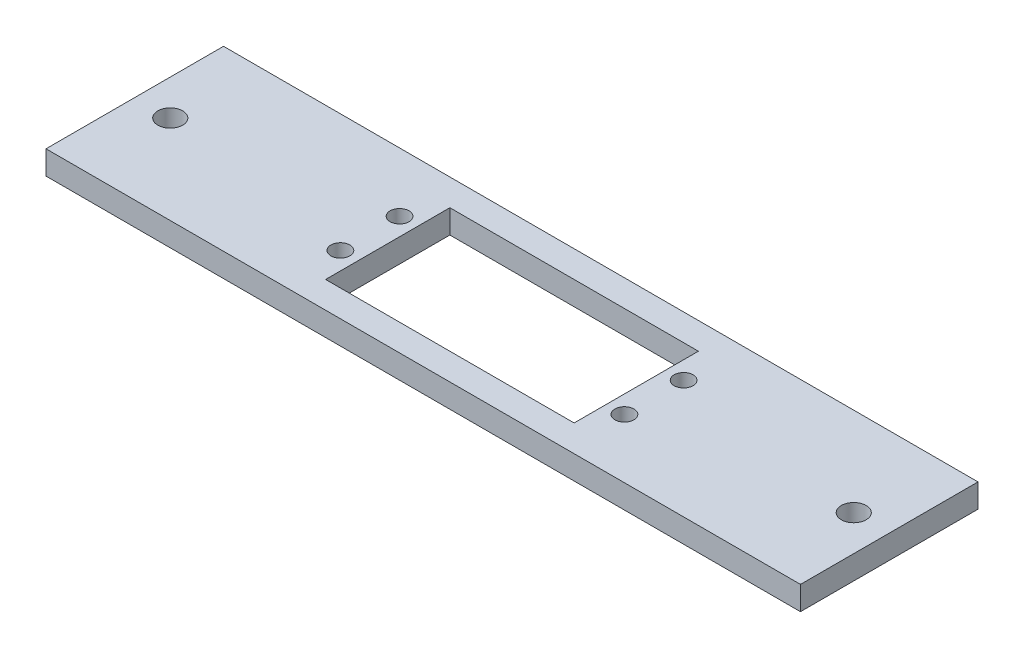
SolidWorks part; units mm, degrees
material "Balsa"
ref_plane "Front Plane" through (0, 0, 0) normal (0, 0, 1) x (1, 0, 0)
ref_plane "Top Plane" through (0, 0, 0) normal (0, 1, 0) x (1, 0, 0)
ref_plane "Right Plane" through (0, 0, 0) normal (1, 0, 0) x (0, 0, -1)
sketch "Sketch1" plane through (0, 0, 0) normal (0, 1, 0) x (1, 0, 0)
  line L0 (-21, 10.5) -> (-27.75, 10.5) construction
  line L1 (-21, -10.5) -> (21, -10.5)
  line L2 (-21, -10.5) -> (-21, 10.5)
  line L3 (-21, 10.5) -> (21, 10.5)
  line L4 (21, -10.5) -> (21, 10.5)
  line L5 (-21, -10.5) -> (21, 10.5) construction
  line L6 (-21, 10.5) -> (21, -10.5) construction
  line L7 (-27.75, 10.5) -> (-27.75, -10.5) construction
  line L8 (-27.75, -10.5) -> (-21, -10.5) construction
  line L9 (0, 10.5) -> (0, -10.5) construction
  line L10 (27.75, -10.5) -> (21, -10.5) construction
  line L11 (27.75, 10.5) -> (27.75, -10.5) construction
  line L12 (21, 10.5) -> (27.75, 10.5) construction
  line L13 (-53.9162, 0) -> (53.9162, 0) construction
  line L14 (0, 15) -> (0, -15) construction
  line L15 (-63.75, 15) -> (63.75, 15)
  line L16 (-63.75, 15) -> (-63.75, -15)
  line L17 (-63.75, -15) -> (63.75, -15)
  line L18 (63.75, 15) -> (63.75, -15)
  line L19 (-63.75, 0) -> (63.75, 0) construction
  circle A0 centre (-57.75, 0) radius 2.1
  circle A1 centre (57.75, 0) radius 2.1
  point P0 (0, 0)
  point P14 (0, 0)
  point P27 (0, 0)
  dimension "D4" = 4.2
  dimension "D1" = 21
  dimension "D2" = 42
  dimension "D3" = 55.5
  dimension "D5" = 30
  dimension "D6" = 30
  dimension "D7" = 6
extrude "Boss-Extrude1" add sketch "Sketch1" along normal blind 4
sketch "Sketch2" plane through (0, 4, 0) normal (0, 1, 0) x (1, 0, 0)
  line L0 (0, 15) -> (0, -15) construction
  line L1 (63.75, 15) -> (-63.75, 15) construction
  line L2 (-63.75, -15) -> (63.75, -15) construction
  line L3 (-63.75, 0) -> (63.75, 0) construction
  line L4 (-63.75, 15) -> (-63.75, -15) construction
  line L5 (63.75, -15) -> (63.75, 15) construction
  line L6 (-24, 15) -> (-24, -15) construction
  line L7 (24, 15) -> (24, -15) construction
  circle A0 centre (-24, 5) radius 1.6
  circle A1 centre (-24, -5) radius 1.6
  circle A2 centre (24, -5) radius 1.6
  circle A3 centre (24, 5) radius 1.6
  dimension "D1" = 3.2
  dimension "D3" = 48
  dimension "D2" = 10
extrude "Cut-Extrude1" cut sketch "Sketch2" against normal through all
